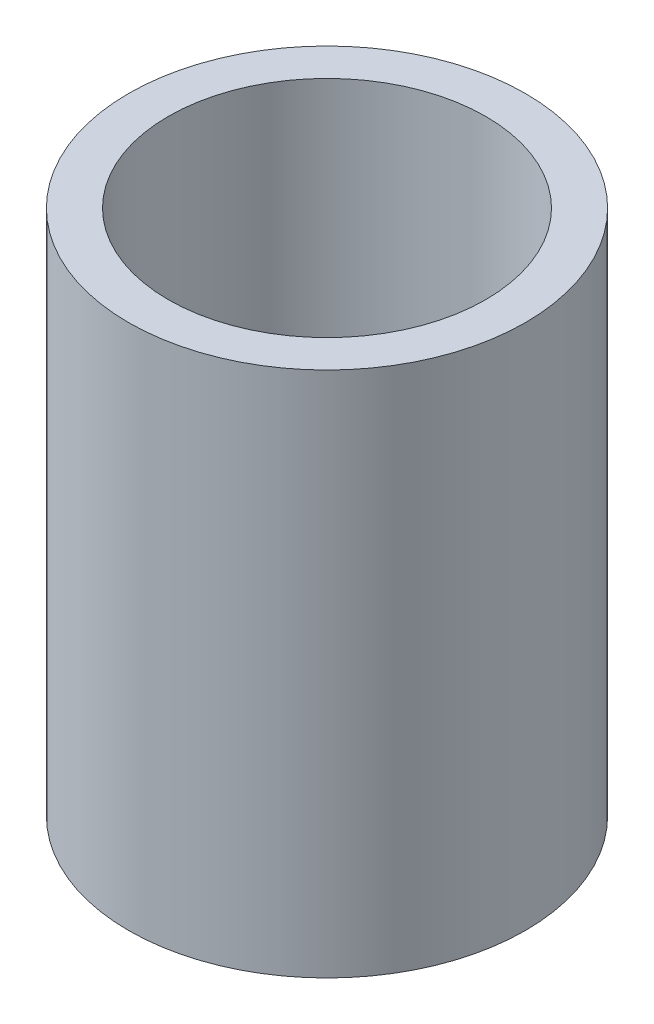
SolidWorks part; units mm, degrees
ref_plane "Płaszczyzna przednia" through (0, 0, 0) normal (0, 0, 1) x (1, 0, 0)
ref_plane "Płaszczyzna górna" through (0, 0, 0) normal (0, 1, 0) x (1, 0, 0)
ref_plane "Płaszczyzna prawa" through (0, 0, 0) normal (1, 0, 0) x (0, 0, -1)
sketch "Sketch1" plane through (0, 0, 0) normal (0, 0, 1) x (1, 0, 0)
  line L0 (0, 0) -> (0, 19.9) construction
  line L1 (6, 19.9) -> (0, 19.9) construction
  line L2 (6, 0) -> (7.5, 0)
  line L3 (6, 0) -> (6, 19.9)
  line L4 (6, 19.9) -> (7.5, 19.9)
  line L5 (7.5, 0) -> (7.5, 19.9)
  dimension "D1" = 6
  dimension "D2" = 1.5
  dimension "D3" = 19.9
revolve "Revolve1" add sketch "Sketch1" angle 360 about L0
